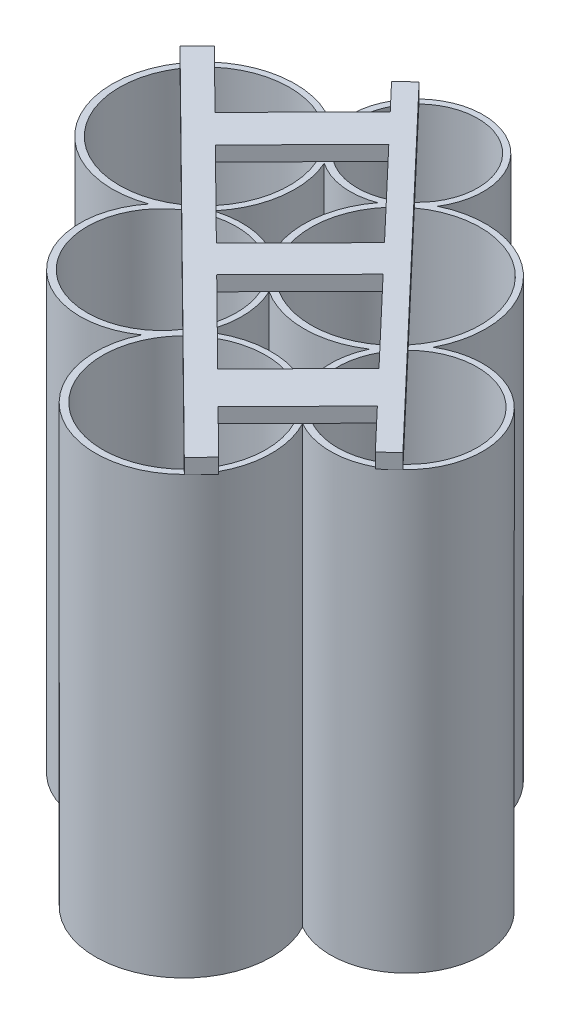
SolidWorks part; units mm, degrees
ref_plane "Front Plane" through (0, 0, 0) normal (0, 0, 1) x (1, 0, 0)
ref_plane "Top Plane" through (0, 0, 0) normal (0, 1, 0) x (1, 0, 0)
ref_plane "Right Plane" through (0, 0, 0) normal (1, 0, 0) x (0, 0, -1)
sketch "Sketch1" plane through (0, 0, 0) normal (0, 1, 0) x (1, 0, 0)
  circle A0 centre (22.572, 43.5293) radius 8.15
  circle A1 centre (6.2008, 31.0909) radius 11.5
  circle A6 centre (51.661, 13.0686) radius 9.45
  circle A7 centre (18.9197, 12.5914) radius 10.1
  circle A8 centre (36.0053, -1.4476) radius 11.05
  circle A9 centre (35.5128, 27.639) radius 11.45
  circle A10 centre (35.5128, 27.639) radius 12.3
  circle A11 centre (36.0053, -1.4476) radius 11.9
  circle A12 centre (51.661, 13.0686) radius 10.3
  circle A13 centre (18.9197, 12.5914) radius 10.95
  circle A14 centre (6.2008, 31.0909) radius 12.35
  circle A16 centre (22.572, 43.5293) radius 9
  dimension "D1" = 16.3
  dimension "D2" = 23
  dimension "D3" = 18.9
  dimension "D4" = 20.2
  dimension "D5" = 22.1
  dimension "D6" = 22.9
  dimension "D7" = 24.6
  dimension "D8" = 20.6
  dimension "D9" = 23.8
  dimension "D10" = 21.9
  dimension "D11" = 24.7
  dimension "D12" = 18
extrude "Boss-Extrude4" add sketch "Sketch1" along normal blind 59 contours A11 | A12 | A10 | A13 | A14 | A16
sketch "Sketch4" plane through (0, 59, 0) normal (0, 1, 0) x (1, 0, 0)
  circle A0 centre (22.6113, 43.5899) radius 8.15
  circle A1 centre (6.2401, 31.1515) radius 11.5
  circle A2 centre (51.7003, 13.1292) radius 9.45
  circle A3 centre (18.959, 12.652) radius 10.1
  circle A4 centre (36.0446, -1.387) radius 11.05
  circle A5 centre (35.5521, 27.6996) radius 11.45
  circle A6 centre (35.5521, 27.6996) radius 12.3
  circle A7 centre (36.0446, -1.387) radius 11.9
  circle A8 centre (51.7003, 13.1292) radius 10.3
  circle A9 centre (18.959, 12.652) radius 10.95
  circle A10 centre (6.2401, 31.1515) radius 12.35
  circle A11 centre (22.6113, 43.5899) radius 9
  dimension "D1" = 23
  dimension "D2" = 18.9
  dimension "D3" = 20.2
  dimension "D4" = 22.1
  dimension "D5" = 22.9
  dimension "D6" = 24.6
  dimension "D7" = 20.6
  dimension "D8" = 23.8
  dimension "D9" = 21.9
  dimension "D10" = 24.7
  dimension "D11" = 18
extrude "Cut-Extrude2" cut sketch "Sketch4" against normal blind 57 contours A0 | A1 | A3 | A5 | A2 | A4
sketch "Sketch5" plane through (0, 59, 0) normal (0, 1, 0) x (1, 0, 0)
  line L0 (-3.9881, 38.0701) -> (44.47, -9.8116)
  line L1 (-3.9881, 38.0701) -> (-1.6815, 40.4045)
  line L2 (44.47, -9.8116) -> (46.7766, -7.4773)
  line L3 (-1.6815, 40.4045) -> (46.7766, -7.4773)
  line L4 (58.6889, 5.5387) -> (16.3709, 50.052)
  line L5 (58.6889, 5.5387) -> (56.7783, 3.7224)
  line L6 (16.3709, 50.052) -> (14.4603, 48.2357)
  line L7 (56.7783, 3.7224) -> (14.4603, 48.2357)
  line L8 (17.9263, 44.5899) -> (6.1471, 32.6689)
  line L9 (17.9263, 44.5899) -> (21.7615, 40.8004)
  line L10 (6.1471, 32.6689) -> (9.9823, 28.8794)
  line L11 (21.7615, 40.8004) -> (9.9823, 28.8794)
  line L12 (21.5591, 17.4403) -> (32.862, 28.8794)
  line L13 (21.5591, 17.4403) -> (25.2751, 13.7685)
  line L14 (32.862, 28.8794) -> (36.5781, 25.2075)
  line L15 (25.2751, 13.7685) -> (36.5781, 25.2075)
  line L16 (36.3828, 2.793) -> (47.2277, 13.7685)
  line L17 (36.3828, 2.793) -> (40.8124, -1.584)
  line L18 (47.2277, 13.7685) -> (51.6574, 9.3915)
  line L19 (40.8124, -1.584) -> (51.6574, 9.3915)
  arc A0 (14.0545, 40.622) -> (10.4075, 19.4795) centre (6.2008, 31.0909) ccw construction
  arc A1 (25.2583, 3.6626) -> (46.5057, 4.1516) centre (36.0053, -1.4476) ccw construction
  arc A2 (46.5057, 4.1516) -> (46.4062, 21.9273) centre (51.661, 13.0686) ccw construction
  arc A3 (30.1815, 38.7236) -> (14.0545, 40.622) centre (22.572, 43.5293) ccw construction
  circle M11 centre (6.2401, 31.1515) radius 11.5
  circle M14 centre (22.6113, 43.5899) radius 8.15
  arc M15 (30.1815, 38.7236) -> (14.0545, 40.622) centre (22.572, 43.5293) ccw
extrude "Boss-Extrude5" add sketch "Sketch5" along normal blind 2 contours L7 L4 M14 M15 | L7 L6 M15 | L3 L1 L0 M11 | L12 L14 L15 L13 | L11 L10 L8 L9 | L16 L18 L19 L17
